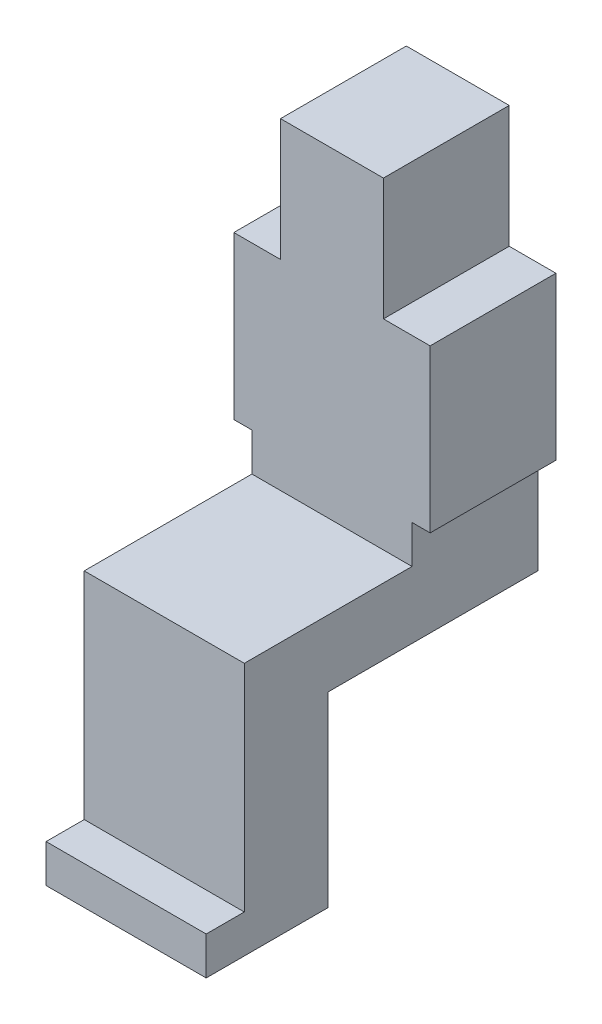
SolidWorks part; units mm, degrees
ref_plane "Front Plane" through (0, 0, 0) normal (0, 0, 1) x (1, 0, 0)
ref_plane "Top Plane" through (0, 0, 0) normal (0, 1, 0) x (1, 0, 0)
ref_plane "Right Plane" through (0, 0, 0) normal (1, 0, 0) x (0, 0, -1)
sketch "Sketch2" plane through (0, 0, 0) normal (1, 0, 0) x (0, 0, -1)
  line L0 (-560, -130) -> (210, -130)
  line L1 (210, -130) -> (210, 570)
  line L2 (210, 570) -> (-120, 570)
  line L3 (-120, 570) -> (-120, 45)
  line L4 (-120, 45) -> (-560, 45)
  line L5 (-560, 45) -> (-560, -130)
  dimension "D1" = 700
  dimension "D2" = 210
  dimension "D3" = 130
  dimension "D4" = 330
  dimension "D5" = 770
  dimension "D6" = 175
extrude "Boss-Extrude1" add sketch "Sketch2" along normal mid plane 420
sketch "Sketch3" plane through (0, 570, 0) normal (0, 1, 0) x (1, 0, 0)
  line L0 (210, 210) -> (-210, 210) construction
  line L1 (-135, 210) -> (135, 210)
  line L2 (-135, 210) -> (-135, -120)
  line L3 (-135, -120) -> (135, -120)
  line L4 (135, 210) -> (135, -120)
  line L5 (210, -120) -> (-210, -120) construction
  line L6 (-210, 210) -> (-210, -120) construction
  dimension "D1" = 270
  dimension "D2" = 75
extrude "Boss-Extrude2" add sketch "Sketch3" along normal blind 320
sketch "Sketch4" plane through (0, 0, 0) normal (1, 0, 0) x (0, 0, -1)
  line L0 (210, -130) -> (210, 570) construction
  line L1 (-120, 570) -> (210, 570)
  line L2 (-120, 570) -> (-120, 145)
  line L3 (-120, 145) -> (210, 145)
  line L4 (210, 570) -> (210, 145)
  dimension "D1" = 425
extrude "Boss-Extrude3" add sketch "Sketch4" along normal mid plane 515
sketch "Sketch5" plane through (0, -130, 0) normal (0, -1, 0) x (1, 0, 0)
  line L0 (210, 560) -> (210, -210) construction
  line L1 (-210, 560) -> (210, 560)
  line L2 (-210, 560) -> (-210, 340)
  line L3 (-210, 340) -> (210, 340)
  line L4 (210, 560) -> (210, 340)
  dimension "D1" = 220
extrude "Boss-Extrude4" add sketch "Sketch5" along normal blind 490
sketch "Sketch6" plane through (0, 0, 560) normal (0, 0, 1) x (1, 0, 0)
  line L0 (210, 45) -> (210, -620) construction
  line L1 (-210, -620) -> (210, -620)
  line L2 (-210, -620) -> (-210, -520)
  line L3 (-210, -520) -> (210, -520)
  line L4 (210, -620) -> (210, -520)
  dimension "D1" = 100
extrude "Boss-Extrude5" add sketch "Sketch6" along normal blind 100
